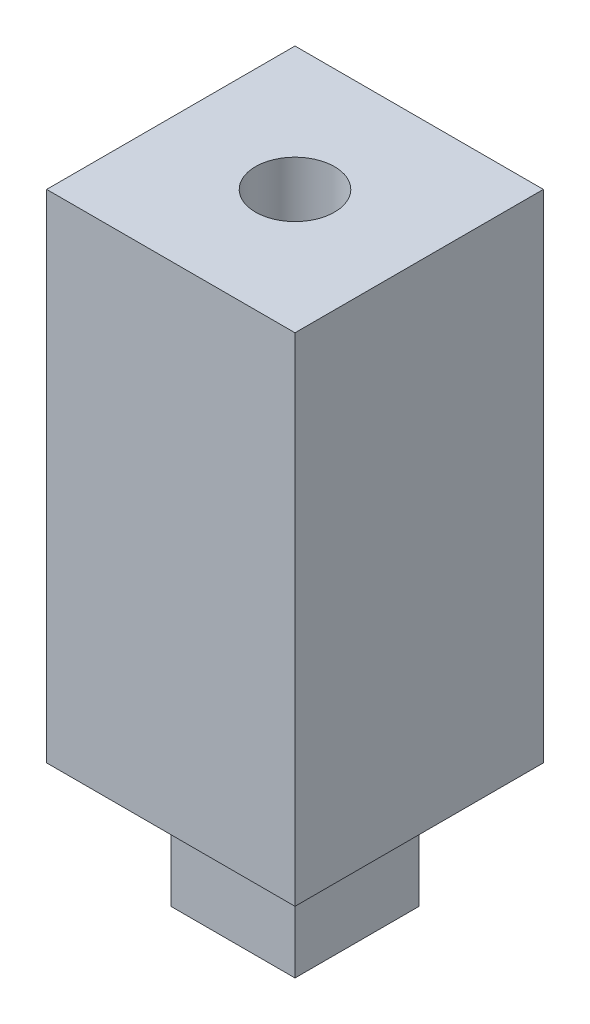
SolidWorks part; units mm, degrees
material "Plain Carbon Steel"
ref_plane "Front Plane" through (0, 0, 0) normal (0, 0, 1) x (1, 0, 0)
ref_plane "Top Plane" through (0, 0, 0) normal (0, 1, 0) x (1, 0, 0)
ref_plane "Right Plane" through (0, 0, 0) normal (1, 0, 0) x (0, 0, -1)
sketch "Sketch1" plane through (0, 0, 0) normal (0, 1, 0) x (1, 0, 0)
  line L1 (-6.35, -6.35) -> (6.35, -6.35)
  line L2 (-6.35, -6.35) -> (-6.35, 6.35)
  line L3 (-6.35, 6.35) -> (6.35, 6.35)
  line L4 (6.35, -6.35) -> (6.35, 6.35)
  line L5 (0, 6.35) -> (0, -6.35) construction
  line L6 (-6.35, 0) -> (6.35, 0) construction
  point P0 (0, 0)
  dimension "D1" = 12.7
  dimension "D2" = 12.7
extrude "Boss-Extrude1" add sketch "Sketch1" along normal blind 25.4
sketch "Sketch2" plane through (0, 0, 0) normal (0, -1, 0) x (1, 0, 0)
  line L1 (3.175, 3.175) -> (-3.175, 3.175)
  line L2 (3.175, 3.175) -> (3.175, -3.175)
  line L3 (3.175, -3.175) -> (-3.175, -3.175)
  line L4 (-3.175, 3.175) -> (-3.175, -3.175)
  line L5 (0, -3.175) -> (0, 3.175) construction
  line L6 (3.175, 0) -> (-3.175, 0) construction
  point P0 (0, 0)
  dimension "D1" = 6.35
  dimension "D2" = 6.35
extrude "Boss-Extrude2" add sketch "Sketch2" along normal blind 6.35
hole_wizard "#10-32 Tapped Hole2" positions "Sketch4" profile "Sketch3" tap size "#10-32" standard "ANSI Inch"
sketch "Sketch4" plane through (0, -6.35, 0) normal (0, -1, 0) x (-1, 0, 0)
  point P0 (0, 0)
sketch "Sketch3" plane through (0, -6.35, 0) normal (1, 0, 0) x (0, 0, -1)
  line L0 (0, 0) -> (0, 13.9133)
  line L1 (0, 13.9133) -> (2.0193, 12.7)
  line L2 (2.0193, 12.7) -> (2.0193, 0)
  line L5 (2.0193, 0) -> (0, 0)
  line L10 (0, 13.9133) -> (-2.0193, 12.7) construction
  line L11 (0, -6.35) -> (0, 107.95) construction
  dimension "Tap Drill Dia." = 4.0386
  dimension "Tap Drill Depth" = 12.7
  dimension "Drill Angle" = 118
cosmetic thread "Hole Thread1" parameters "D1"=9.652, "D2"=4.826
hole_wizard "#10-32 Tapped Hole3" positions "Sketch6" profile "Sketch5" tap size "#10-32" standard "ANSI Inch"
sketch "Sketch6" plane through (0, 25.4, 0) normal (0, 1, 0) x (1, 0, 0)
  point P0 (0, 0)
sketch "Sketch5" plane through (0, 25.4, 0) normal (1, 0, 0) x (0, 0, 1)
  line L0 (0, 0) -> (0, 13.9133)
  line L1 (0, 13.9133) -> (2.0193, 12.7)
  line L2 (2.0193, 12.7) -> (2.0193, 0)
  line L5 (2.0193, 0) -> (0, 0)
  line L10 (0, 13.9133) -> (-2.0193, 12.7) construction
  line L11 (0, -6.35) -> (0, 107.95) construction
  dimension "Tap Drill Dia." = 4.0386
  dimension "Tap Drill Depth" = 12.7
  dimension "Drill Angle" = 118
cosmetic thread "Hole Thread2" parameters "D1"=9.652, "D2"=4.826
